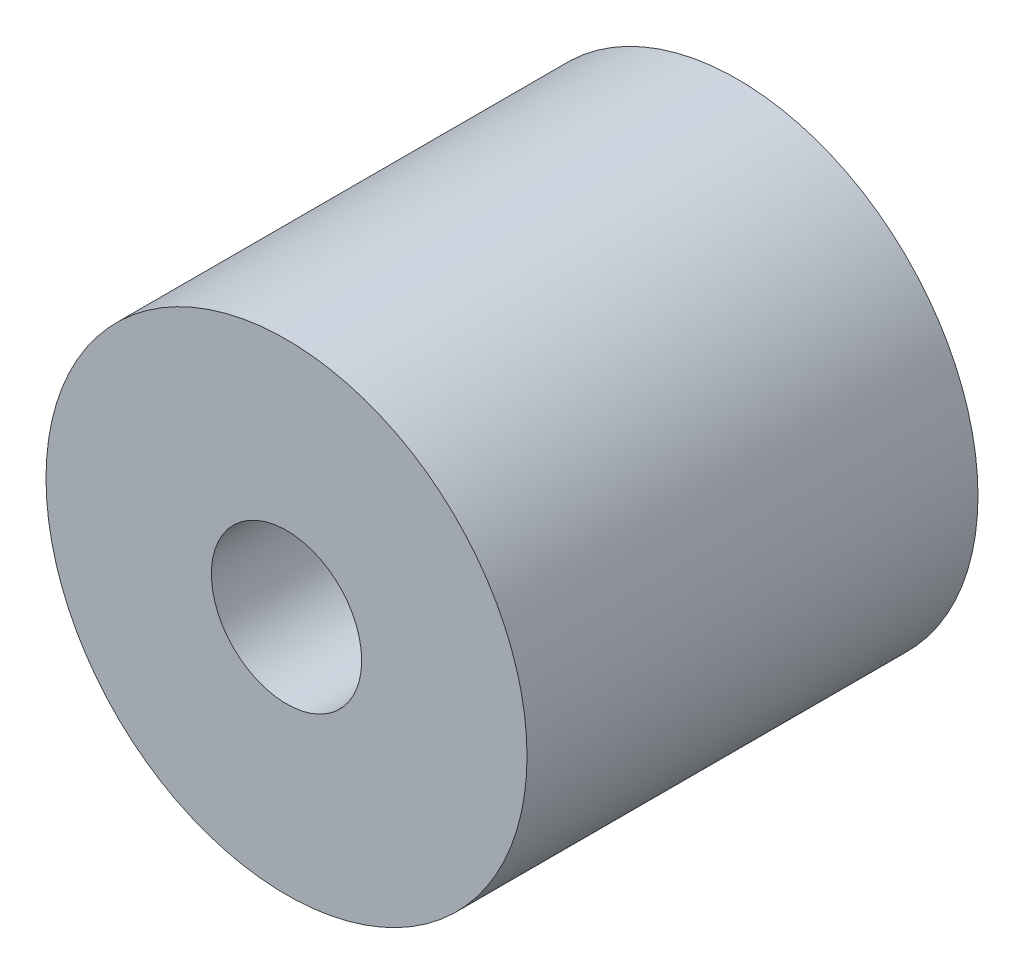
SolidWorks part; units mm, degrees
ref_plane "前视基准面" through (0, 0, 0) normal (0, 0, 1) x (1, 0, 0)
ref_plane "上视基准面" through (0, 0, 0) normal (0, 1, 0) x (1, 0, 0)
ref_plane "右视基准面" through (0, 0, 0) normal (1, 0, 0) x (0, 0, -1)
other "Configuration Table"
sketch "草图1" plane through (0, 0, 0) normal (0, 0, 1) x (1, 0, 0)
  circle A0 centre (0, 0) radius 8
  circle A1 centre (0, 0) radius 2.5
extrude "Foot_M6_tapped_15" add sketch "草图1" along normal blind 15
